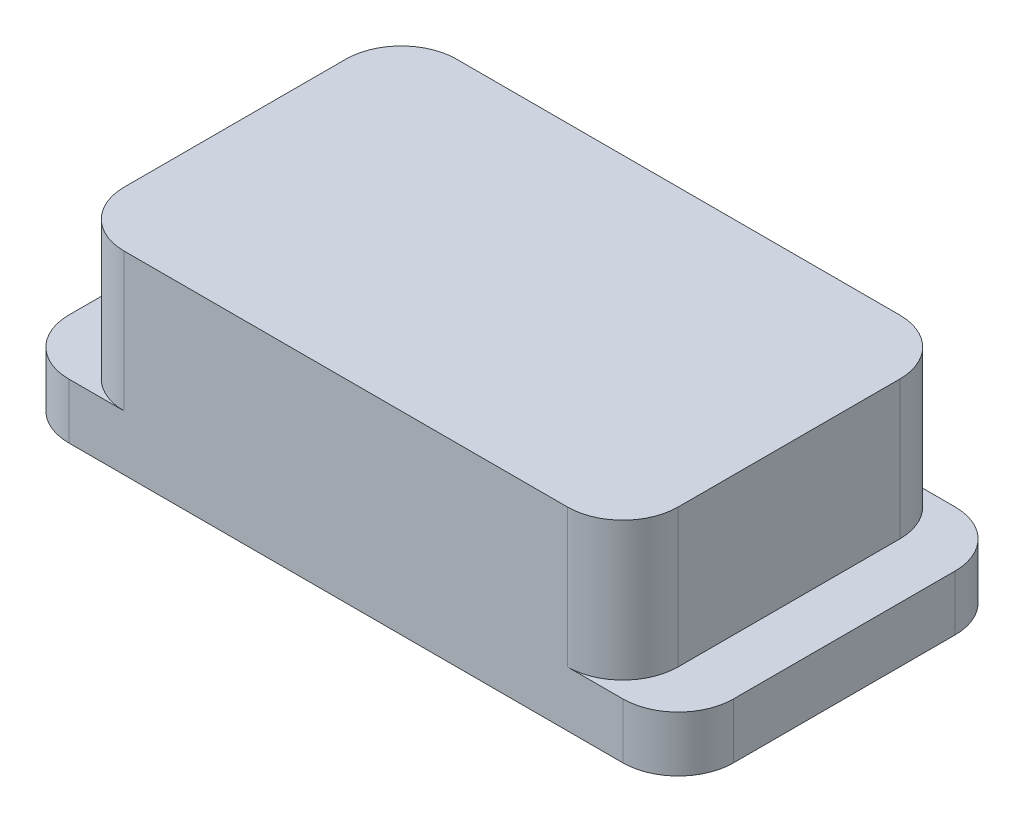
SolidWorks part; units mm, degrees
ref_plane "Front Plane" through (0, 0, 0) normal (0, 0, 1) x (1, 0, 0)
ref_plane "Top Plane" through (0, 0, 0) normal (0, 1, 0) x (1, 0, 0)
ref_plane "Right Plane" through (0, 0, 0) normal (1, 0, 0) x (0, 0, -1)
sketch "Sketch1" plane through (0, 0, 0) normal (0, 1, 0) x (1, 0, 0)
  line L1 (-5, 3) -> (5, 3)
  line L2 (-5, 3) -> (-5, -3)
  line L3 (-5, -3) -> (5, -3)
  line L4 (5, 3) -> (5, -3)
  line L5 (-5, 3) -> (5, -3) construction
  line L6 (-5, -3) -> (5, 3) construction
  point P0 (0, 0)
  dimension "D1" = 10
  dimension "D2" = 6
extrude "Boss-Extrude1" add sketch "Sketch1" along normal blind 2.5
sketch "Sketch2" plane through (0, 0, 0) normal (0, -1, 0) x (1, 0, 0)
  line L1 (6, 3) -> (-6, 3)
  line L2 (6, 3) -> (6, -3)
  line L3 (6, -3) -> (-6, -3)
  line L4 (-6, 3) -> (-6, -3)
  line L5 (6, 3) -> (-6, -3) construction
  line L6 (6, -3) -> (-6, 3) construction
  point P0 (0, 0)
  dimension "D1" = 6
  dimension "D2" = 12
extrude "Boss-Extrude2" add sketch "Sketch2" along normal blind 1
fillet "Fillet1" radius 1 8 edges at (-5, 1.25, 3) (-6, -0.5, -3) (-5, 1.25, -3) (6, -0.5, 3) (5, 1.25, 3) (5, 1.25, -3) (6, -0.5, -3) (-6, -0.5, 3)
